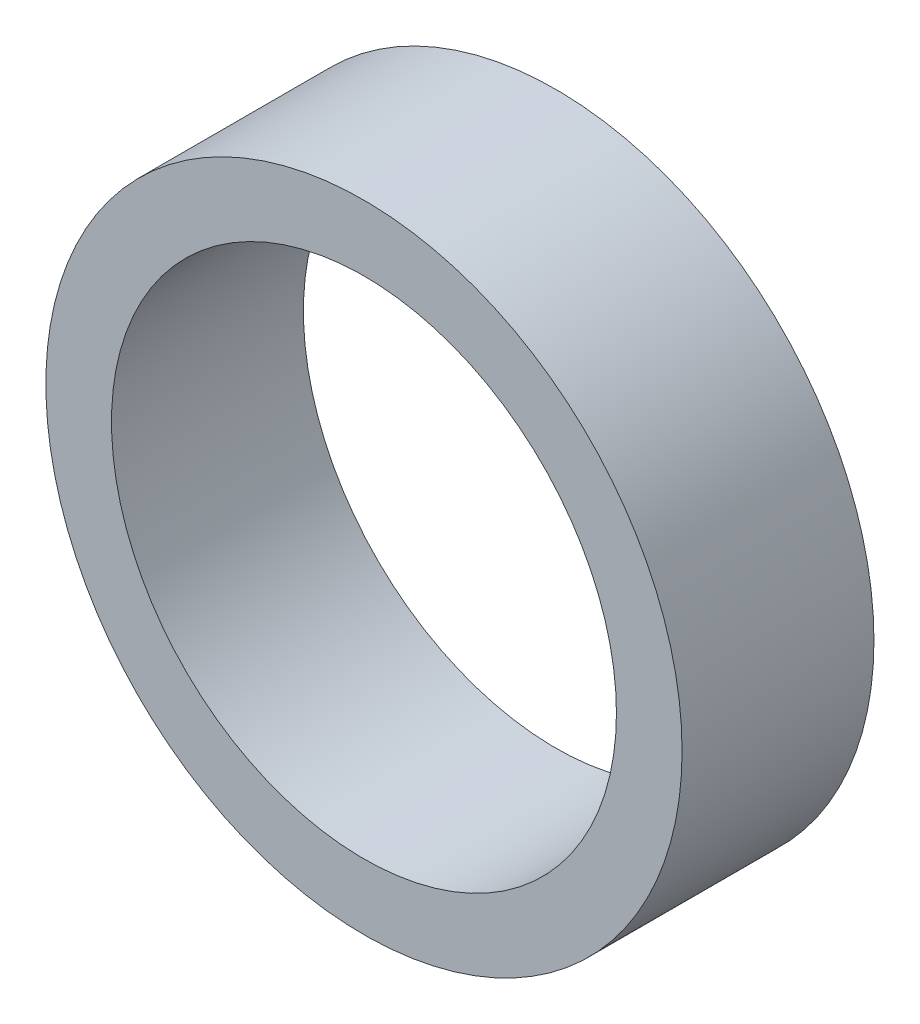
SolidWorks part; units mm, degrees
ref_plane "Alzado" through (0, 0, 0) normal (0, 0, 1) x (1, 0, 0)
ref_plane "Planta" through (0, 0, 0) normal (0, 1, 0) x (1, 0, 0)
ref_plane "Vista lateral" through (0, 0, 0) normal (1, 0, 0) x (0, 0, -1)
sketch "Croquis1" plane through (0, 0, 0) normal (0, 0, 1) x (1, 0, 0)
  circle A0 centre (0, 0) radius 31.5
  circle A1 centre (0, 0) radius 25
  dimension "D1" = 63
  dimension "D2" = 50
extrude "Saliente-Extruir1" add sketch "Croquis1" against normal blind 19
